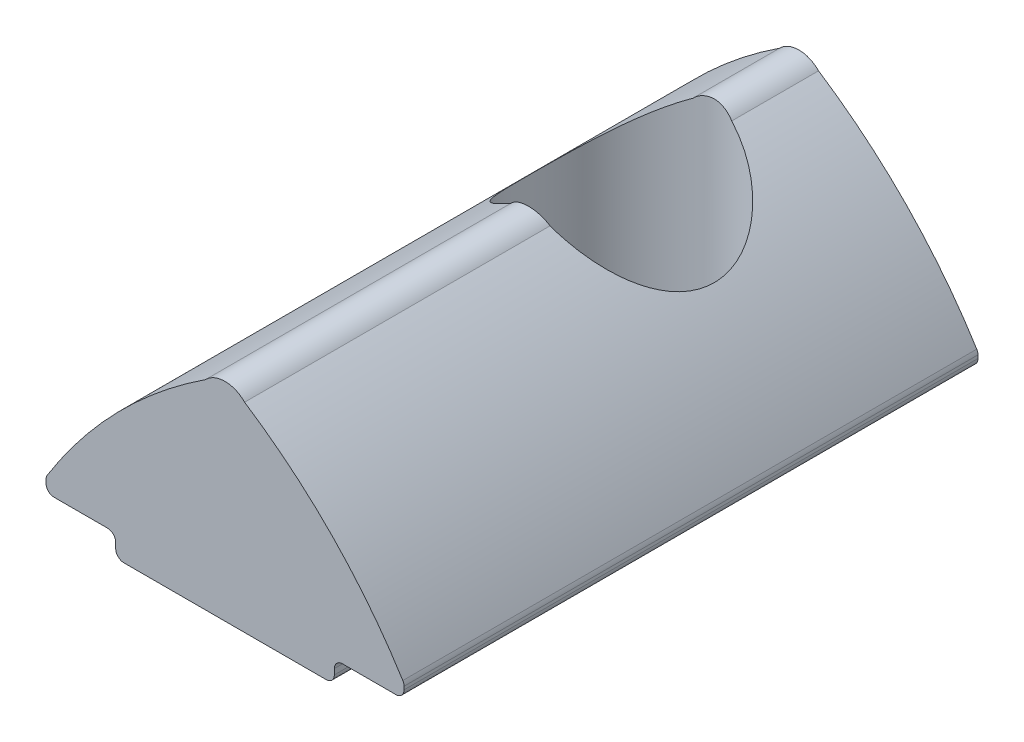
SolidWorks part; units mm, degrees
ref_plane "前视基准面" through (0, 0, 0) normal (0, 0, 1) x (1, 0, 0)
ref_plane "上视基准面" through (0, 0, 0) normal (0, 1, 0) x (1, 0, 0)
ref_plane "右视基准面" through (0, 0, 0) normal (1, 0, 0) x (0, 0, -1)
sketch "草图1" plane through (0, 0, 0) normal (0, 0, 1) x (1, 0, 0)
  line B0 (-3.7, 0) -> (3.7, 0)
  line B1 (6.55, 1.1) -> (6.55, 1.2147)
  line B2 (-6.55, 1.1) -> (-6.55, 1.2147)
  line B3 (4, 0.3) -> (4, 0.5)
  line B4 (-4, 0.3) -> (-4, 0.5)
  line B5 (-6.25, 0.8) -> (-4.3, 0.8)
  line B6 (4.3, 0.8) -> (6.25, 0.8)
  arc B7 (6.25, 0.8) -> (6.55, 1.1) centre (6.25, 1.1) ccw
  arc B8 (-6.55, 1.1) -> (-6.25, 0.8) centre (-6.25, 1.1) ccw
  arc B9 (3.7, 0) -> (4, 0.3) centre (3.7, 0.3) ccw
  arc B10 (-4, 0.3) -> (-3.7, 0) centre (-3.7, 0.3) ccw
  arc B11 (-4, 0.5) -> (-4.3, 0.8) centre (-4.3, 0.5) ccw
  arc B12 (4.3, 0.8) -> (4, 0.5) centre (4.3, 0.5) ccw
  arc B13 (0.7168, 7.2972) -> (-0.7168, 7.2972) centre (0, 6.6) ccw
  arc B14 (6.5048, 1.3731) -> (0.7168, 7.2972) centre (-9.796, -8.7634) ccw
  arc B15 (6.55, 1.2147) -> (6.5048, 1.3731) centre (6.25, 1.2147) ccw
  arc B16 (-0.7168, 7.2972) -> (-6.5048, 1.3731) centre (9.796, -8.7634) ccw
  arc B17 (-6.5048, 1.3731) -> (-6.55, 1.2147) centre (-6.25, 1.2147) ccw
sketch_block_instance "A$C58DE158A-1"
sketch_block "A$C58DE158A"
extrude "凸台-拉伸1" add sketch "草图1" along normal mid plane 21
sketch "草图3" plane through (0, 0, 0) normal (0, -1, 0) x (1, 0, 0)
  line L0 (-3.7, 10.5) -> (3.7, 10.5) construction
  point P0 (0, -4)
  dimension "D1" = 14.5
hole_wizard "M8 螺纹孔1" positions "3D草图1" profile "草图4" tap size "M8" standard "Iso" end condition through all
sketch3d "3D草图1"
  point P0 (0, 0, -4)
sketch "草图4" plane through (0, 0, -4) normal (1, 0, 0) x (0, 0, -1)
  line L0 (0, 0) -> (0, 7.6)
  line L1 (0, 7.6) -> (3.4, 7.6)
  line L2 (3.4, 7.6) -> (3.4, 0)
  line L5 (3.4, 0) -> (0, 0)
  line L11 (0, -6.35) -> (0, 107.95) construction
  dimension "通孔螺纹孔钻头直径" = 6.8
  dimension "通孔螺纹孔钻头深度" = 7.6
cosmetic thread "孔螺蚊线1" parameters "D2"=8
